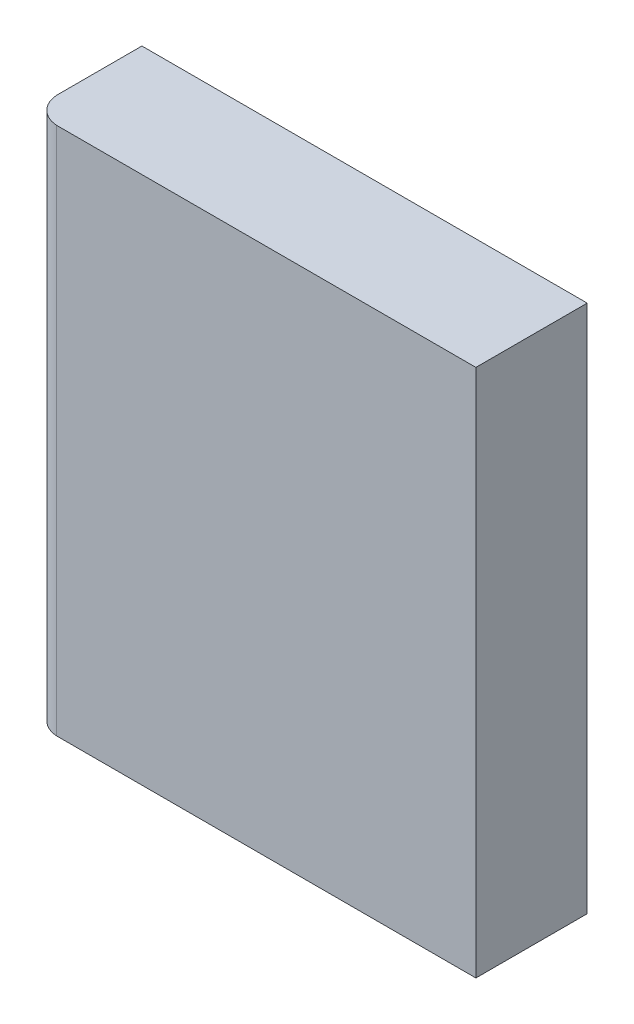
SolidWorks part; units mm, degrees
ref_plane "Front Plane" through (0, 0, 0) normal (0, 0, 1) x (1, 0, 0)
ref_plane "Top Plane" through (0, 0, 0) normal (0, 1, 0) x (1, 0, 0)
ref_plane "Right Plane" through (0, 0, 0) normal (1, 0, 0) x (0, 0, -1)
sketch "Sketch1" plane through (0, 0, 0) normal (0, 1, 0) x (1, 0, 0)
  line L1 (-12.7633, 2.9228) -> (12.6367, 2.9228)
  line L2 (-12.7633, 2.9228) -> (-12.7633, -1.9284)
  line L3 (-11.2804, -3.4272) -> (12.6367, -3.4272)
  line L4 (12.6367, 2.9228) -> (12.6367, -3.4272)
  arc A0 (-12.7633, -1.9284) -> (-11.2804, -3.4272) centre (-11.1781, -1.843) ccw
  point P6 (0, 0)
extrude "Boss-Extrude1" add sketch "Sketch1" along normal blind 30.1625
